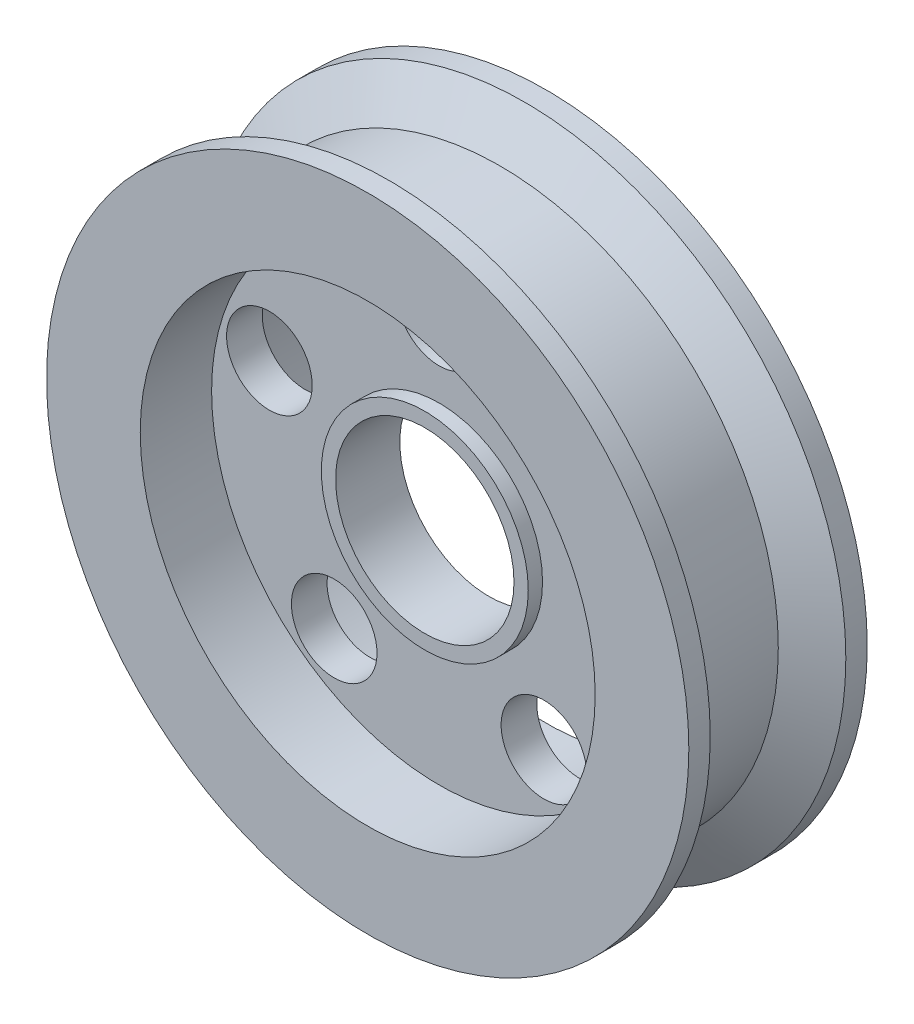
SolidWorks part; units mm, degrees
ref_plane "Front Plane" through (0, 0, 0) normal (0, 0, 1) x (1, 0, 0)
ref_plane "Top Plane" through (0, 0, 0) normal (0, 1, 0) x (1, 0, 0)
ref_plane "Right Plane" through (0, 0, 0) normal (1, 0, 0) x (0, 0, -1)
sketch "Sketch1" plane through (0, 0, 0) normal (0, 0, 1) x (1, 0, 0)
  circle A0 centre (0, 0) radius 45
  circle A1 centre (0, 0) radius 12.5
  dimension "D1" = 90
  dimension "D2" = 25
extrude "Boss-Extrude1" add sketch "Sketch1" along normal mid plane 25
sketch "Sketch2" plane through (0, 0, 12.5) normal (0, 0, 1) x (1, 0, 0)
  circle A0 centre (0, 0) radius 31.875
  dimension "D1" = 63.75
extrude "Cut-Extrude1" cut sketch "Sketch2" against normal blind 10
mirror "Mirror1" about plane through (0, 0, 0) normal (0, 0, 1) of "Cut-Extrude1"
sketch "Sketch3" plane through (0, 0, 2.5) normal (0, 0, 1) x (1, 0, 0)
  circle A0 centre (0, 25) radius 6
  dimension "D1" = 12
  dimension "D2" = 25
extrude "Cut-Extrude2" cut sketch "Sketch3" against normal through all
pattern_circular "CirPattern1" count 5 over 360 about axis through (0, 0, 0) along (0, 0, 1) of "Cut-Extrude2"
sketch "Sketch4" plane through (0, 0, 2.5) normal (0, 0, 1) x (1, 0, 0)
  circle A0 centre (0, 0) radius 14.5
  circle A1 centre (0, 0) radius 12.5 construction
  circle A2 centre (0, 0) radius 12.5
  dimension "D1" = 29
extrude "Boss-Extrude2" add sketch "Sketch4" along normal blind 2 and the other way blind 7
sketch "Sketch5" plane through (0, 0, 0) normal (0, 1, 0) x (1, 0, 0)
  line L0 (0, 0) -> (0, 34.4667) construction
  line L1 (45, 9.5) -> (39, 6.0359)
  line L2 (45, -12.5) -> (45, 12.5) construction
  line L3 (39, 6.0359) -> (39, -6.0359)
  line L4 (39, -6.0359) -> (45, -9.5)
  line L5 (45, -9.5) -> (45, 9.5)
  dimension "D1" = 3
  dimension "D2" = 3
  dimension "D3" = 6
  dimension "D4" = 120
  dimension "D5" = 60
revolve "Cut-Revolve1" cut sketch "Sketch5" angle 360 about L0
